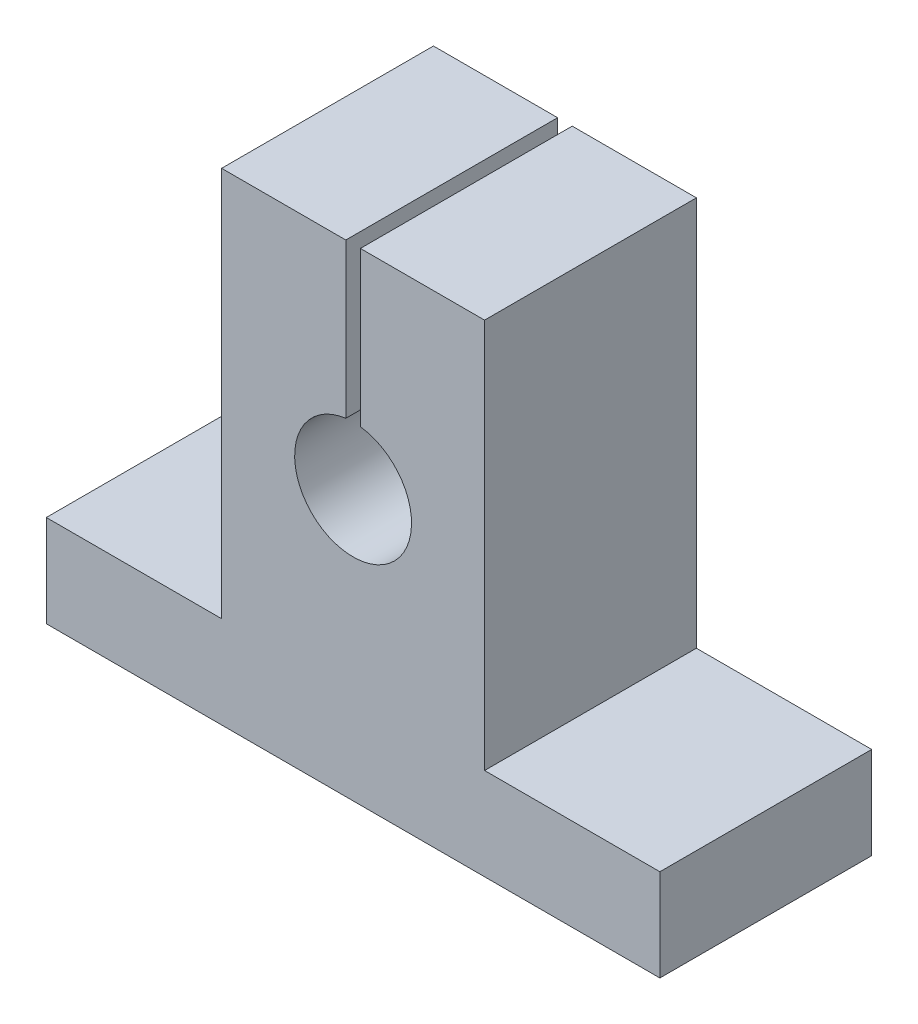
SolidWorks part; units mm, degrees
ref_plane "Front Plane" through (0, 0, 0) normal (0, 0, 1) x (1, 0, 0)
ref_plane "Top Plane" through (0, 0, 0) normal (0, 1, 0) x (1, 0, 0)
ref_plane "Right Plane" through (0, 0, 0) normal (1, 0, 0) x (0, 0, -1)
sketch "Sketch1" plane through (0, 0, 0) normal (0, 0, 1) x (1, 0, 0)
  line L0 (-21, 0) -> (21, 0)
  line L1 (21, 0) -> (21, 6.3)
  line L2 (21, 6.3) -> (9, 6.3)
  line L3 (9, 6.3) -> (9, 33)
  line L4 (9, 33) -> (0.5, 33)
  line L5 (-9, 33) -> (-9, 6.3)
  line L6 (-9, 6.3) -> (-21, 6.3)
  line L7 (-21, 6.3) -> (-21, 0)
  line L8 (0, 33) -> (0, 18.461) construction
  line L9 (-0.5, 33) -> (-0.5, 22.4297)
  line L10 (0.5, 33) -> (0.5, 22.4297)
  line L11 (-0.5, 33) -> (-9, 33)
  line L12 (-0.5, 33) -> (-0.5, 18.461) construction
  line L13 (0.5, 33) -> (0.5, 18.461) construction
  arc A0 (-0.5, 22.4297) -> (0.5, 22.4297) centre (0, 18.461) ccw
  point P4 (0, 0)
  dimension "D1" = 42
  dimension "D2" = 6.3
  dimension "D3" = 12
  dimension "D4" = 12
  dimension "D5" = 26.7
  dimension "D6" = 0.5
  dimension "D7" = 0.5
extrude "Boss-Extrude1" add sketch "Sketch1" along normal blind 14.5
